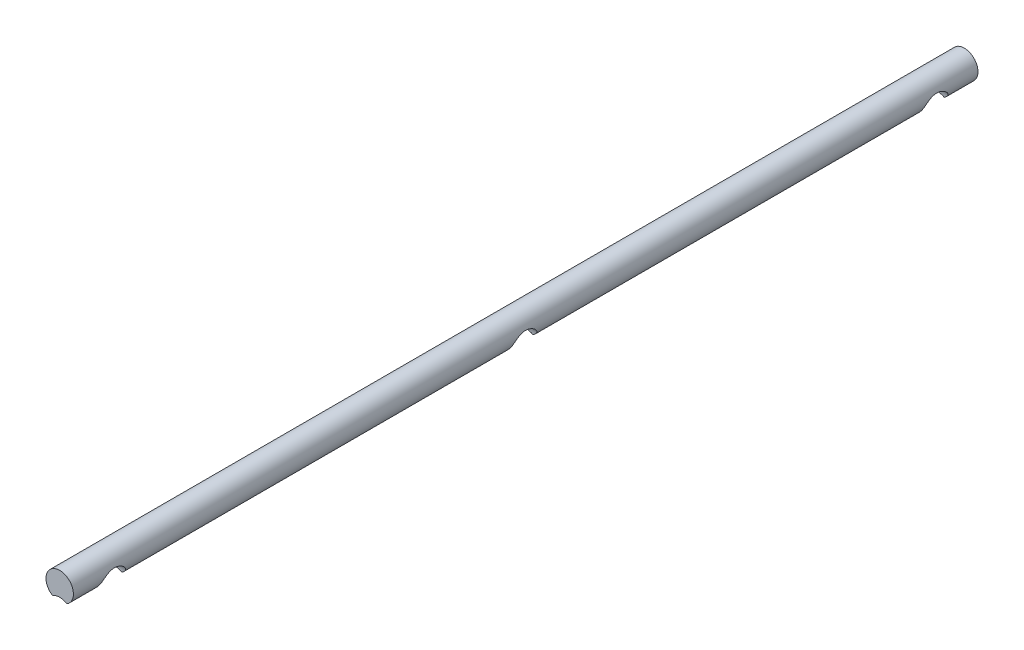
SolidWorks part; units mm, degrees
ref_plane "Спереди" through (0, 0, 0) normal (0, 0, 1) x (1, 0, 0)
ref_plane "Сверху" through (0, 0, 0) normal (0, 1, 0) x (1, 0, 0)
ref_plane "Справа" through (0, 0, 0) normal (1, 0, 0) x (0, 0, -1)
sketch "Эскиз1" plane through (0, 0, 0) normal (0, 0, 1) x (1, 0, 0)
  line L0 (0, 100) -> (0, -70) construction
  circle A0 centre (0, 0) radius 100
  circle A2 centre (0, -175) radius 105
  point P6 (0, 0)
  dimension "D1" = 200
  dimension "D3" = 210
  dimension "D2" = 170
extrude "Бобышка-Вытянуть1" add sketch "Эскиз1" along normal mid plane 6600 contours L0 A0 A2 | A0 L0 A2
sketch "Эскиз2" plane through (0, 0, 0) normal (1, 0, 0) x (0, 0, -1)
  line L0 (-3300, 100) -> (-3300, -84.5714) construction
  line L1 (-3300, -84.5714) -> (3300, -84.5714) construction
  line L2 (0, 0) -> (0, 114.413) construction
  circle A0 centre (-3000, -84.5714) radius 100
  circle A1 centre (3000, -84.5714) radius 100
  circle A2 centre (0, -84.5714) radius 100
  dimension "D2" = 200
  dimension "D1" = 300
  dimension "D3" = 3000
extrude "Вырез-Вытянуть1" cut sketch "Эскиз2" against normal mid plane 6000
sketch "Эскиз3" plane through (0, 0, 0) normal (0, 1, 0) x (1, 0, 0)
  line L0 (-100, -3300) -> (100, -3300) construction
  line L1 (0, -2920.923) -> (0, -3079.077) construction
  line L2 (-79.077, -3000) -> (79.077, -3000) construction
  line L3 (0, 0) -> (163.9977, 0) construction
  line L4 (-79.077, 3000) -> (79.077, 3000) construction
  line L5 (0, 2920.923) -> (0, 3079.077) construction
  line L6 (0, 79.077) -> (0, -79.077) construction
  line L7 (79.077, 0) -> (-79.077, 0) construction
  circle A0 centre (0, -3000) radius 79.077 construction
  circle A1 centre (0, 3000) radius 79.077 construction
  circle A2 centre (0, 0) radius 79.077 construction
  dimension "D2" = 158.1541
  dimension "D1" = 300
  dimension "D3" = 3000
equation "\"Длина\"= 6000 + 600"
equation "\"D1@Бобышка-Вытянуть1\"=\"Длина\""
